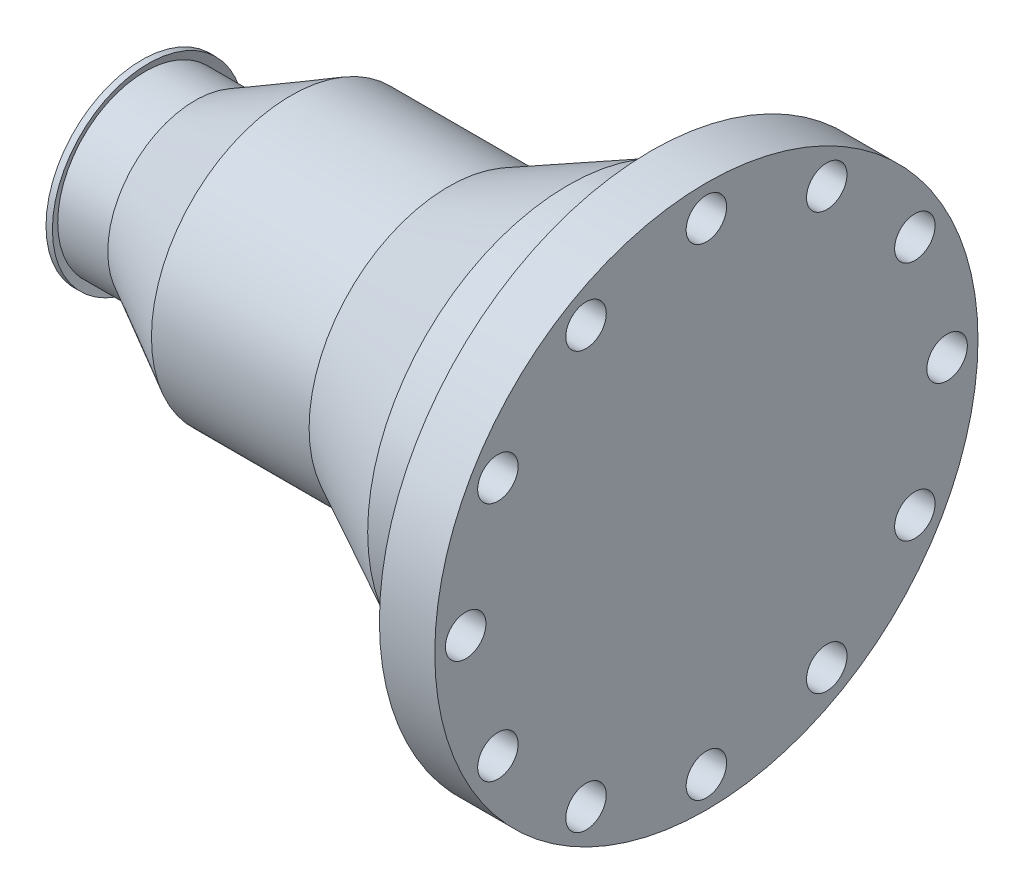
SolidWorks part; units mm, degrees
ref_plane "Спереди" through (0, 0, 0) normal (0, 0, 1) x (1, 0, 0)
ref_plane "Сверху" through (0, 0, 0) normal (0, 1, 0) x (1, 0, 0)
ref_plane "Справа" through (0, 0, 0) normal (1, 0, 0) x (0, 0, -1)
sketch "Эскиз1" plane through (0, 0, 0) normal (0, 0, 1) x (1, 0, 0)
  line L0 (0, 0) -> (265, 0)
  line L1 (0, 0) -> (0, 45)
  line L2 (0, 45) -> (3, 45)
  line L3 (3, 45) -> (1.5, 41)
  line L4 (1.5, 41) -> (25, 41)
  line L5 (25, 41) -> (70, 65.5)
  line L6 (70, 65.5) -> (144, 65.5)
  line L7 (144, 65.5) -> (200, 94)
  line L8 (200, 94) -> (220, 94)
  line L9 (220, 94) -> (220, 95)
  line L10 (220, 95) -> (239, 95)
  line L11 (239, 95) -> (239, 100)
  line L12 (239, 100) -> (239, 127.5)
  line L13 (239, 127.5) -> (265, 127.5)
  line L14 (265, 127.5) -> (265, 0)
revolve "Повернуть1" add sketch "Эскиз1" angle 360 about L0
sketch "Эскиз2" plane through (0, 0, 0) normal (0, 0, 1) x (1, 0, 0)
  line L0 (0, 0) -> (220, 0)
  line L1 (220, 94) -> (220, -94) construction
  line L2 (0, 0) -> (0, 31)
  line L3 (0, 45) -> (0, -45) construction
  line L4 (0, 31) -> (42, 31)
  line L5 (42, 31) -> (70, 38.5026)
  line L6 (70, 65.5) -> (70, -65.5) construction
  line L7 (90, 52.5) -> (142, 52.5)
  line L8 (143.5, 52.5) -> (146.6699, 52.5)
  line L9 (147.6699, 55) -> (200, 55)
  line L10 (200, 94) -> (200, -94) construction
  line L11 (200, 55) -> (200, 38.5026)
  line L12 (200, 38.5026) -> (220, 38.5026)
  line L13 (220, 38.5026) -> (220, 0)
  arc A0 (70, 38.5026) -> (90, 52.5) centre (107.8022, 5.7765) cw
  arc A1 (142, 52.5) -> (143.5, 52.5) centre (142.75, 49.8032) cw
  arc A2 (146.6699, 52.5) -> (147.6699, 55) centre (147.5934, 53.5806) cw
revolve "Вырез-Повернуть1" cut sketch "Эскиз2" angle 360 about L0
sketch "Эскиз3" plane through (0, 0, 0) normal (1, 0, 0) x (0, 0, -1)
  circle A0 centre (0, 113) radius 9.5
extrude "Вырез-Вытянуть1" cut sketch "Эскиз3" along normal through all
sketch "Эскиз4" plane through (0, 0, 0) normal (1, 0, 0) x (0, 0, -1)
  circle A0 centre (-56.5, 97.8609) radius 9.5
extrude "Вырез-Вытянуть2" cut sketch "Эскиз4" along normal through all
sketch "Эскиз5" plane through (0, 0, 0) normal (1, 0, 0) x (0, 0, -1)
  circle A0 centre (-97.8609, 56.5) radius 9.5
extrude "Вырез-Вытянуть3" cut sketch "Эскиз5" along normal through all
sketch "Эскиз6" plane through (0, 0, 0) normal (1, 0, 0) x (0, 0, -1)
  circle A0 centre (-113, 0) radius 9.5
extrude "Вырез-Вытянуть4" cut sketch "Эскиз6" along normal through all
sketch "Эскиз7" plane through (0, 0, 0) normal (1, 0, 0) x (0, 0, -1)
  circle A0 centre (-97.8609, -56.5) radius 9.5
extrude "Вырез-Вытянуть5" cut sketch "Эскиз7" along normal through all
sketch "Эскиз8" plane through (0, 0, 0) normal (1, 0, 0) x (0, 0, -1)
  circle A0 centre (-56.5, -97.8609) radius 9.5
extrude "Вырез-Вытянуть6" cut sketch "Эскиз8" along normal through all
sketch "Эскиз9" plane through (0, 0, 0) normal (1, 0, 0) x (0, 0, -1)
  circle A0 centre (0, -113) radius 9.5
extrude "Вырез-Вытянуть7" cut sketch "Эскиз9" along normal through all
sketch "Эскиз10" plane through (0, 0, 0) normal (1, 0, 0) x (0, 0, -1)
  circle A0 centre (56.5, -97.8609) radius 9.5
extrude "Вырез-Вытянуть8" cut sketch "Эскиз10" along normal through all
sketch "Эскиз11" plane through (0, 0, 0) normal (1, 0, 0) x (0, 0, -1)
  circle A0 centre (97.8609, -56.5) radius 9.5
extrude "Вырез-Вытянуть9" cut sketch "Эскиз11" along normal through all
sketch "Эскиз12" plane through (0, 0, 0) normal (1, 0, 0) x (0, 0, -1)
  circle A0 centre (113, 0) radius 9.5
extrude "Вырез-Вытянуть10" cut sketch "Эскиз12" along normal through all
sketch "Эскиз13" plane through (0, 0, 0) normal (1, 0, 0) x (0, 0, -1)
  circle A0 centre (97.8609, 56.5) radius 9.5
extrude "Вырез-Вытянуть11" cut sketch "Эскиз13" along normal through all
sketch "Эскиз14" plane through (0, 0, 0) normal (1, 0, 0) x (0, 0, -1)
  circle A0 centre (56.5, 97.8609) radius 9.5
extrude "Вырез-Вытянуть12" cut sketch "Эскиз14" along normal through all
